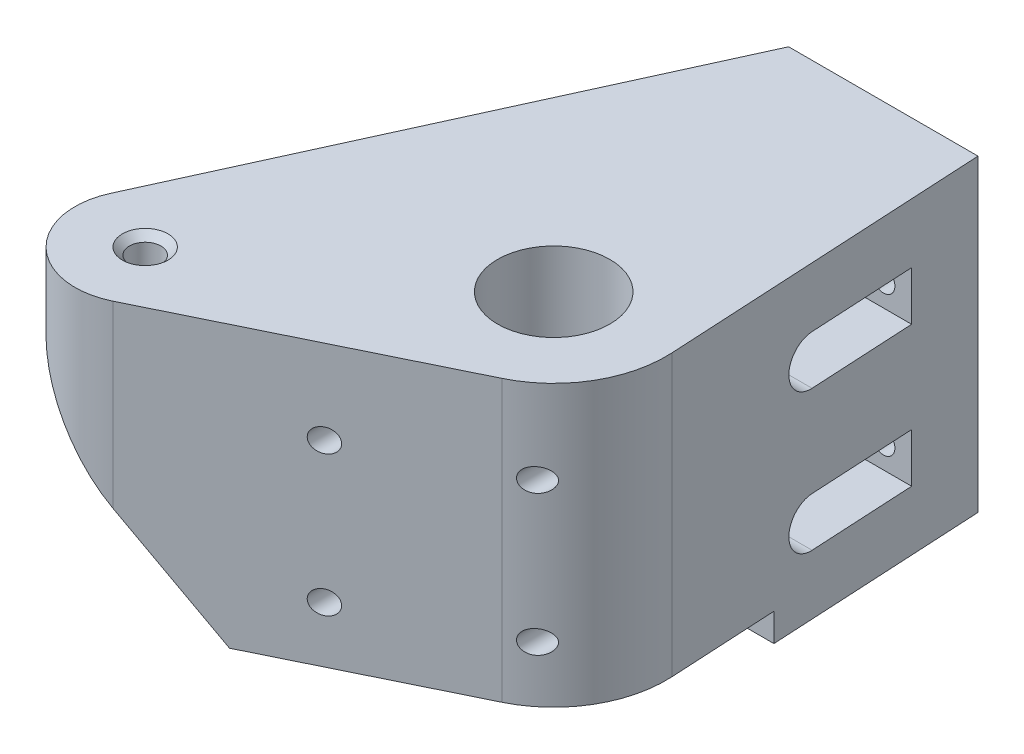
SolidWorks part; units mm, degrees
material "PET"
ref_plane "Front Plane" through (0, 0, 0) normal (0, 0, 1) x (1, 0, 0)
ref_plane "Top Plane" through (0, 0, 0) normal (0, 1, 0) x (1, 0, 0)
ref_plane "Right Plane" through (0, 0, 0) normal (1, 0, 0) x (0, 0, -1)
sketch "Sketch1" plane through (0, 0, 0) normal (0, 1, 0) x (1, 0, 0)
  line L0 (0, 0) -> (0, 47) construction
  line L1 (-13.5, 0) -> (13.5, 0)
  line L2 (13.5, 0) -> (15.977, 46.1423)
  line L6 (-30.2615, 79.5856) -> (7.0216, 61.377)
  line L7 (-43.7514, 66.457) -> (-13.5, 0)
  circle A0 centre (0, 47) radius 8
  arc A1 (15.977, 46.1423) -> (7.0216, 61.377) centre (0, 47) ccw
  circle A2 centre (-34.65, 70.6) radius 2.25
  arc A3 (-30.2615, 79.5856) -> (-43.7514, 66.457) centre (-34.65, 70.6) ccw
  dimension "D2" = 32
  dimension "D3" = 16
  dimension "D4" = 47
  dimension "D5" = 34.65
  dimension "D6" = 23.6
  dimension "D7" = 4.5
  dimension "D8" = 20
  dimension "D1" = 27
extrude "Boss-Extrude1" add sketch "Sketch1" along normal blind 44
sketch "Sketch2" plane through (0, 0, 0) normal (0, -1, 0) x (1, 0, 0)
  line L0 (0, -30.75) -> (15.1507, -30.75)
  line L1 (13.5, 0) -> (15.977, -46.1423) construction
  line L2 (15.1507, -30.75) -> (16.5451, -56.7258)
  line L8 (0, -30.75) -> (-44.65, -30.75)
  line L9 (-44.65, -30.75) -> (-44.65, -86.6128)
  line L10 (-44.65, -86.6128) -> (16.5451, -56.7258)
  line L11 (7.0216, -61.377) -> (-30.2615, -79.5856) construction
  arc A1 (-43.7514, -66.457) -> (-30.2615, -79.5856) centre (-34.65, -70.6) ccw construction
  circle A2 centre (0, -47) radius 8 construction
  dimension "D1" = 16.25
extrude "Cut-Extrude4" cut sketch "Sketch2" against normal blind 4
sketch "Sketch4" plane through (0, 0, 0) normal (0, 0, 1) x (1, 0, 0)
  line L0 (-16, 0) -> (-44.65, 37)
  line L1 (-27.4975, 0) -> (-13.5, 0) construction
  line L2 (-44.65, 44) -> (-44.65, 4) construction
  line L3 (-44.65, 37) -> (-44.65, 0)
  line L4 (-44.65, 0) -> (-16, 0)
  dimension "D1" = 16
  dimension "D2" = 7
extrude "Cut-Extrude5" cut sketch "Sketch4" against normal through all
sketch "Sketch5" plane through (0, 4, 0) normal (0, -1, 0) x (1, 0, 0)
  circle A0 centre (0, -47) radius 12 construction
  dimension "D1" = 24
hole_wizard "Ø4.5 (4.5) Diameter Hole1" positions "Sketch6" profile "Sketch8" hole size "Ø4.5" standard "ANSI Metric"
sketch "Sketch6" plane through (0, 4, 0) normal (0, -1, 0) x (-1, 0, 0)
  circle A0 centre (0, 47) radius 12 construction
  point P0 (0, 35)
  point P4 (0, 59)
  point P6 (12, 47)
  point P8 (-12, 47)
sketch "Sketch8" plane through (0, 4, -35) normal (1, 0, 0) x (0, 0, -1)
  line L0 (0, 0) -> (0, 11.3519)
  line L1 (0, 11.3519) -> (2.25, 10)
  line L2 (2.25, 10) -> (2.25, 0)
  line L5 (2.25, 0) -> (0, 0)
  line L10 (0, 11.3519) -> (-2.25, 10) construction
  line L11 (0, -6.35) -> (0, 107.95) construction
  dimension "Hole Dia." = 4.5
  dimension "Hole Depth" = 10
  dimension "Drill Angle" = 118
chamfer "Chamfer1" distance 1 angle 45 5 edges at (-34.65, 44, -68.35) (0, 4, -37.25) (-12, 4, -49.25) (0, 4, -61.25) (12, 4, -49.25)
sketch "Sketch9" plane through (0, 0, 0) normal (0, 0, 1) x (1, 0, 0)
  line L0 (0, 0) -> (0, 44) construction
  line L1 (-13.5, 44) -> (13.5, 44) construction
  line L2 (13.5, 22) -> (-13.5, 22) construction
  line L3 (13.5, 44) -> (13.5, 0) construction
  line L4 (-13.5, 44) -> (-13.5, 0) construction
  line L6 (10, 32) -> (-10, 32) construction
  line L7 (10, 32) -> (10, 12) construction
  line L8 (10, 12) -> (-10, 12) construction
  line L9 (-10, 32) -> (-10, 12) construction
  line L10 (10, 32) -> (-10, 12) construction
  line L11 (10, 12) -> (-10, 32) construction
  point P11 (0, 22)
  dimension "D1" = 20
  dimension "D2" = 20
hole_wizard "Ø3.3 (3.3) Diameter Hole1" positions "Sketch10" profile "Sketch12" hole size "Ø3.3" standard "ANSI Metric" end condition through all
sketch "Sketch10" plane through (0, 0, 0) normal (0, 0, 1) x (1, 0, 0)
  point P0 (-10, 32)
  point P3 (10, 32)
  point P6 (10, 12)
  point P9 (-10, 12)
sketch "Sketch12" plane through (-10, 32, 0) normal (1, 0, 0) x (0, -1, 0)
  line L0 (0, 0) -> (0, 80.6)
  line L1 (0, 80.6) -> (1.65, 80.6)
  line L2 (1.65, 80.6) -> (1.65, 0)
  line L5 (1.65, 0) -> (0, 0)
  line L11 (0, -6.35) -> (0, 107.95) construction
  dimension "Thru Hole Dia." = 3.3
  dimension "Thru Hole Depth" = 80.6
sketch "Sketch13" plane through (0, 0, 0) normal (1, 0, 0) x (0, 0, -1)
  line L0 (0, 22) -> (46.1423, 22) construction
  line L1 (10, 35.5) -> (25, 35.5)
  line L2 (10, 35.5) -> (10, 28.5)
  line L3 (10, 28.5) -> (25, 28.5)
  line L5 (10, 35.5) -> (25, 28.5) construction
  line L6 (10, 28.5) -> (25, 35.5) construction
  line L7 (10, 15.5) -> (25, 15.5)
  line L8 (10, 15.5) -> (10, 8.5)
  line L9 (10, 8.5) -> (25, 8.5)
  line L11 (10, 15.5) -> (25, 8.5) construction
  line L12 (10, 8.5) -> (25, 15.5) construction
  line L13 (46.1423, 44) -> (46.1423, 4) construction
  line L14 (0, 0) -> (0, 44) construction
  arc A0 (25, 28.5) -> (25, 35.5) centre (25, 32) ccw
  arc A1 (25, 8.5) -> (25, 15.5) centre (25, 12) ccw
  point P0 (17.5, 32)
  point P5 (17.5, 12)
  dimension "D1" = 7
  dimension "D2" = 7
  dimension "D3" = 15
  dimension "D4" = 15
  dimension "D5" = 10
  dimension "D6" = 10
  dimension "D7" = 10
  dimension "D8" = 10
extrude "Cut-Extrude6" cut sketch "Sketch13" against normal through all both and the other way through all
ref_plane "Plane1" through (0, 0, 10) normal (0, 0, 1) x (1, 0, 0)
mirror "Mirror2" about plane through (0, 0, 10) normal (0, 0, 1) of bodies 110
sketch "Sketch14" plane through (0, 44, 0) normal (0, 1, 0) x (1, 0, 0)
  line L0 (-13.5, 0) -> (-43.7514, 66.457)
  line L1 (-30.2615, 79.5856) -> (7.0216, 61.377)
  line L2 (13.5, 0) -> (15.977, 46.1423)
  line L3 (-13.5, 0) -> (13.5, 0)
  arc A0 (15.977, 46.1423) -> (7.0216, 61.377) centre (0, 47) ccw
  arc A1 (-30.2615, 79.5856) -> (-43.7514, 66.457) centre (-34.65, 70.6) ccw
extrude "Cut-Extrude7" cut sketch "Sketch14" against normal through all
